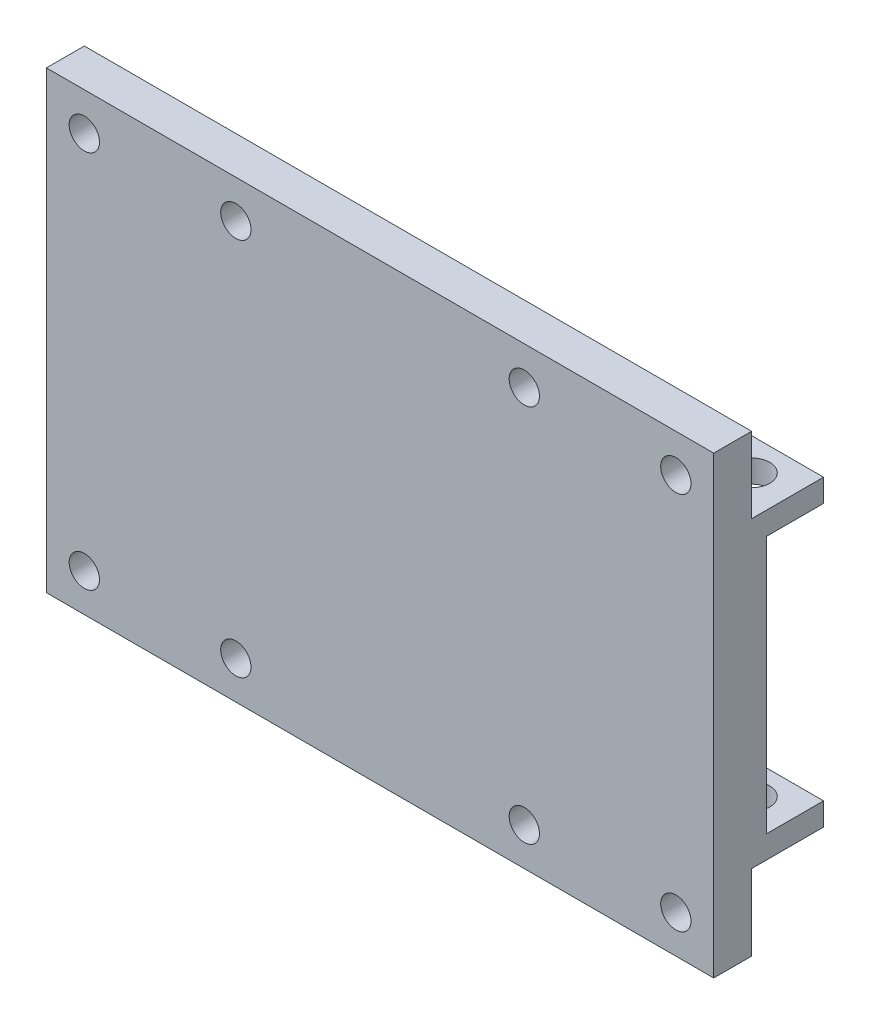
SolidWorks part; units mm, degrees
ref_plane "前视基准面" through (0, 0, 0) normal (0, 0, 1) x (1, 0, 0)
ref_plane "上视基准面" through (0, 0, 0) normal (0, 1, 0) x (1, 0, 0)
ref_plane "右视基准面" through (0, 0, 0) normal (1, 0, 0) x (0, 0, -1)
sketch "草图1" plane through (0, 0, 0) normal (0, 0, 1) x (1, 0, 0)
  line L1 (-70.1804, 23.0718) -> (17.896, 23.0718)
  line L2 (-70.1804, 23.0718) -> (-70.1804, -36.9282)
  line L3 (-70.1804, -36.9282) -> (17.896, -36.9282)
  line L4 (17.896, 23.0718) -> (17.896, -36.9282)
  dimension "D1" = 88.0764
  dimension "D2" = 60
extrude "凸台-拉伸1" add sketch "草图1" along normal blind 5
sketch "草图3" plane through (0, 0, 0) normal (0, 0, -1) x (-1, 0, 0)
  line L0 (-17.896, -36.9282) -> (-17.896, 23.0718) construction
  line L1 (-17.896, 13.0718) -> (14.604, 13.0718)
  line L2 (-17.896, 13.0718) -> (-17.896, 10.0718)
  line L3 (-17.896, 10.0718) -> (14.604, 10.0718)
  line L4 (14.604, 13.0718) -> (14.604, 10.0718)
  line L5 (-17.896, 23.0718) -> (70.1804, 23.0718) construction
  line L7 (70.1804, 23.0718) -> (70.1804, -36.9282) construction
  line L8 (70.1804, 13.0718) -> (37.6804, 13.0718)
  line L9 (70.1804, 13.0718) -> (70.1804, 10.0718)
  line L10 (70.1804, 10.0718) -> (37.6804, 10.0718)
  line L11 (37.6804, 13.0718) -> (37.6804, 10.0718)
  line L12 (70.1804, -36.9282) -> (-17.896, -36.9282) construction
  line L13 (-17.896, -23.9282) -> (14.604, -23.9282)
  line L14 (-17.896, -23.9282) -> (-17.896, -26.9282)
  line L15 (-17.896, -26.9282) -> (14.604, -26.9282)
  line L16 (14.604, -23.9282) -> (14.604, -26.9282)
  line L18 (37.6804, -23.9282) -> (70.1804, -23.9282)
  line L19 (37.6804, -23.9282) -> (37.6804, -26.9282)
  line L20 (37.6804, -26.9282) -> (70.1804, -26.9282)
  line L21 (70.1804, -23.9282) -> (70.1804, -26.9282)
  dimension "D1" = 10
  dimension "D2" = 3
  dimension "D3" = 10
  dimension "D4" = 10
  dimension "D5" = 32.5
  dimension "D6" = 32.5
  dimension "D7" = 3
  dimension "D8" = 32.5
  dimension "D9" = 3
  dimension "D10" = 32.5
  dimension "D11" = 10
  dimension "D12" = 3
extrude "凸台-拉伸2" add sketch "草图3" along normal blind 9.5
sketch "草图4" plane through (0, -26.9282, 0) normal (0, -1, 0) x (-1, 0, 0)
  line L1 (-17.896, 9.5) -> (-17.896, 0) construction
  line L3 (14.604, 9.5) -> (14.604, 0) construction
  line L5 (37.6804, 9.5) -> (37.6804, 0) construction
  line L6 (70.1804, 9.5) -> (70.1804, 0) construction
  line L7 (-17.896, 9.5) -> (14.604, 9.5) construction
  line L8 (37.6804, 9.5) -> (70.1804, 9.5) construction
  circle A0 centre (-12.646, 5.25) radius 2.4
  circle A1 centre (9.354, 5.25) radius 2.4
  circle A2 centre (42.9304, 5.25) radius 2.4
  circle A3 centre (64.9304, 5.25) radius 2.4
  dimension "D1" = 4.25
  dimension "D2" = 5.25
  dimension "D3" = 4.25
  dimension "D4" = 5.25
  dimension "D5" = 4.25
  dimension "D6" = 5.25
  dimension "D7" = 5.25
  dimension "D8" = 4.25
extrude "切除-拉伸2" cut sketch "草图4" against normal blind 100
sketch "草图5" plane through (0, 0, 0) normal (0, 0, -1) x (-1, 0, 0)
  line L1 (-17.896, 10.0718) -> (14.604, 10.0718)
  line L2 (-17.896, 10.0718) -> (-17.896, -23.9282)
  line L3 (-17.896, -23.9282) -> (14.604, -23.9282)
  line L4 (14.604, 10.0718) -> (14.604, -23.9282)
  line L5 (37.6804, 10.0718) -> (70.1804, 10.0718)
  line L6 (37.6804, 10.0718) -> (37.6804, -23.9282)
  line L7 (37.6804, -23.9282) -> (70.1804, -23.9282)
  line L8 (70.1804, 10.0718) -> (70.1804, -23.9282)
extrude "凸台-拉伸3" add sketch "草图5" along normal blind 2
sketch "草图6" plane through (0, 0, 0) normal (0, 0, -1) x (-1, 0, 0)
  line L0 (-17.896, 23.0718) -> (70.1804, 23.0718) construction
  line L1 (-17.896, 13.0718) -> (-17.896, 23.0718) construction
  line L2 (70.1804, -36.9282) -> (-17.896, -36.9282) construction
  line L3 (-17.896, -36.9282) -> (-17.896, -26.9282) construction
  line L4 (70.1804, 23.0718) -> (70.1804, 13.0718) construction
  line L5 (70.1804, -26.9282) -> (70.1804, -36.9282) construction
  circle A0 centre (-12.896, 18.0718) radius 2
  circle A1 centre (-12.896, -31.9282) radius 2
  circle A2 centre (7.104, 18.0718) radius 2
  circle A3 centre (7.104, -31.9282) radius 2
  circle A4 centre (65.1804, 18.0718) radius 2
  circle A5 centre (65.1804, -31.9282) radius 2
  circle A6 centre (45.1804, 18.0718) radius 2
  circle A7 centre (45.1804, -31.9282) radius 2
  dimension "D1" = 5
  dimension "D2" = 5
  dimension "D3" = 5
  dimension "D4" = 5
  dimension "D5" = 20
  dimension "D6" = 5
  dimension "D7" = 20
  dimension "D8" = 5
  dimension "D9" = 5
  dimension "D10" = 5
  dimension "D11" = 5
  dimension "D12" = 5
  dimension "D13" = 20
extrude "切除-拉伸3" cut sketch "草图6" against normal blind 10
